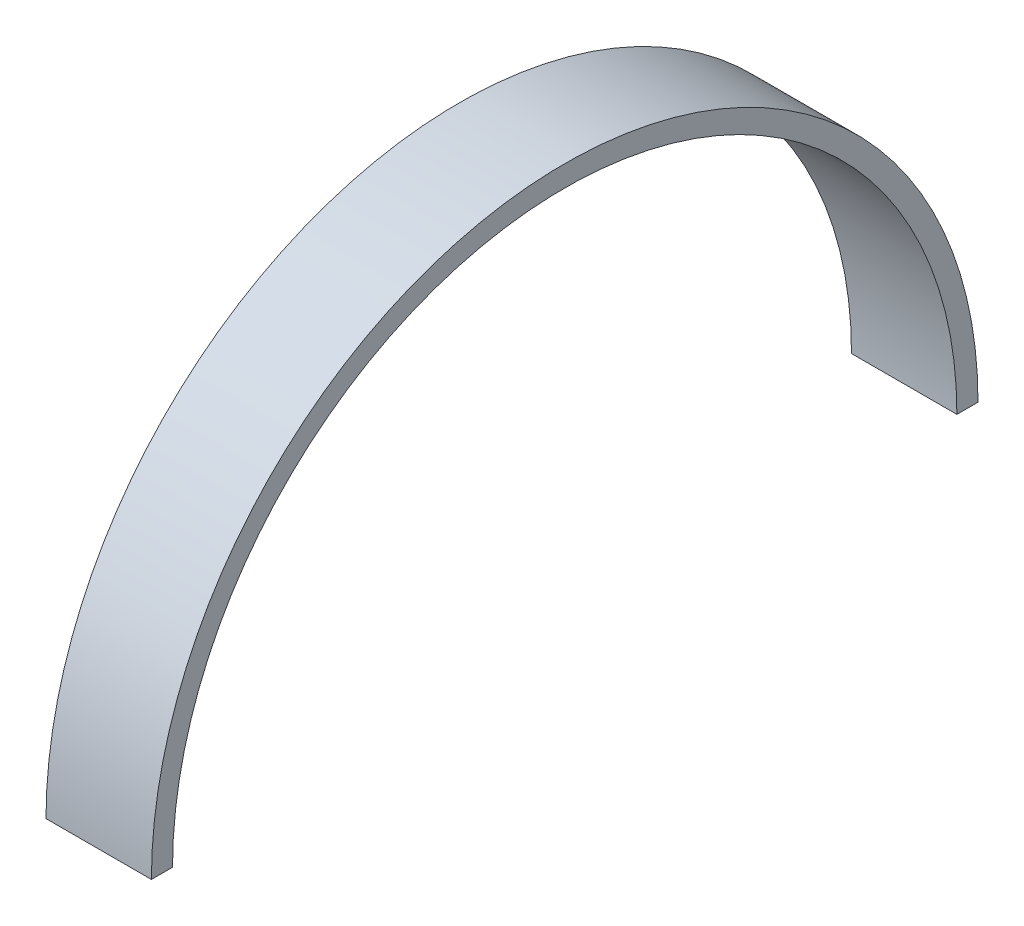
SolidWorks part; units mm, degrees
ref_plane "Спереди" through (0, 0, 0) normal (0, 0, 1) x (1, 0, 0)
ref_plane "Сверху" through (0, 0, 0) normal (0, 1, 0) x (1, 0, 0)
ref_plane "Справа" through (0, 0, 0) normal (1, 0, 0) x (0, 0, -1)
sketch "Эскиз2" plane through (0, 0, 0) normal (1, 0, 0) x (0, 0, -1)
  line L0 (39.2139, 0) -> (37.2115, 0)
  line L1 (-37.2115, 0) -> (-39.2139, 0)
  arc A0 (39.2139, 0) -> (-39.2139, 0) centre (0, 0) ccw
  arc A1 (37.2115, 0) -> (-37.2115, 0) centre (0, 0) ccw
extrude "Бобышка-Вытянуть1" add sketch "Эскиз2" along normal blind 10
